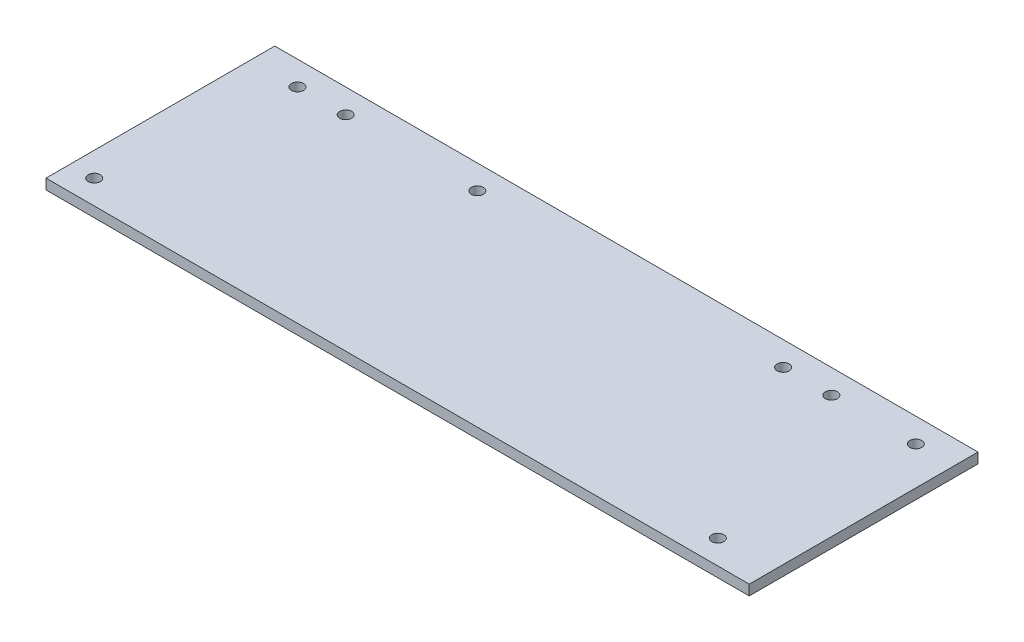
SolidWorks part; units mm, degrees
ref_plane "Front Plane" through (0, 0, 0) normal (0, 0, 1) x (1, 0, 0)
ref_plane "Top Plane" through (0, 0, 0) normal (0, 1, 0) x (1, 0, 0)
ref_plane "Right Plane" through (0, 0, 0) normal (1, 0, 0) x (0, 0, -1)
sketch "Sketch1" plane through (0, 0, 0) normal (0, 1, 0) x (1, 0, 0)
  line L1 (-165.481, -47.5361) -> (164.465, -47.5361)
  line L2 (-165.481, -47.5361) -> (-165.481, 47.5361)
  line L3 (-165.481, 47.5361) -> (164.465, 47.5361)
  line L4 (164.465, -47.5361) -> (164.465, 47.5361)
  line L5 (-165.481, -47.5361) -> (164.465, 47.5361) construction
  line L6 (-165.481, 47.5361) -> (164.465, -47.5361) construction
  line L15 (164.465, -47.5361) -> (114.8334, -47.5361)
  line L16 (164.465, -47.5361) -> (164.465, -42.1259)
  line L19 (-165.481, 47.5361) -> (-205.867, 47.5361)
  line L20 (-165.481, 47.5361) -> (-165.481, -47.5361)
  line L21 (-165.481, -47.5361) -> (-205.867, -47.5361)
  line L22 (-205.867, 47.5361) -> (-205.867, -47.5361)
  line L23 (-205.867, -47.5361) -> (164.465, -47.5361)
  line L24 (-205.867, -47.5361) -> (-205.867, -72.9361)
  line L25 (-205.867, -72.9361) -> (164.465, -72.9361)
  line L26 (164.465, -47.5361) -> (164.465, -72.9361)
  line L34 (86.7283, -47.6885) -> (91.8337, -47.6885) construction
  line L35 (86.5759, -47.5361) -> (91.9861, -47.5361)
  line L36 (86.5759, -47.5361) -> (86.5759, -60.2361)
  line L37 (86.5759, -60.2361) -> (91.9861, -60.2361)
  line L38 (91.9861, -47.5361) -> (91.9861, -60.2361)
  line L39 (91.8337, -47.6885) -> (91.8337, -60.0837) construction
  line L40 (86.7283, -60.0837) -> (91.8337, -60.0837) construction
  line L41 (86.7283, -47.6885) -> (86.7283, -60.0837) construction
  line L42 (-73.787, 47.5361) -> (-73.787, -42.1259)
  line L44 (62.5475, -42.1259) -> (62.5475, 47.5361)
  circle A0 centre (-155.829, 34.8361) radius 3.175
  circle A1 centre (-86.487, 34.8361) radius 3.175
  circle A2 centre (99.949, 34.8361) radius 3.175
  circle A3 centre (144.399, 34.8361) radius 3.175
  circle A4 centre (-181.229, 34.8361) radius 3.175
  circle A5 centre (-193.167, -60.2361) radius 3.175
  circle A6 centre (135.255, -60.2361) radius 3.175
  circle A7 centre (74.549, 34.8361) radius 3.175
  dimension "D10" = 69.342
  dimension "D18" = 40.386
  dimension "D22" = 6.35
  dimension "D23" = 12.7
  dimension "D25" = 12.7
  dimension "D27" = 12.7
  dimension "D6" = 25.4
  dimension "D1" = 329.946
  dimension "D2" = 95.0722
  dimension "D4" = 20.066
  dimension "D5" = 44.45
  dimension "D11" = 9.652
  dimension "D14" = 12.7
  dimension "D15" = 12.7
  dimension "D16" = 12.7
  dimension "D17" = 12.7
  dimension "D19" = 25.4
  dimension "D20" = 12.7
  dimension "D21" = 25.4
  dimension "D24" = 12.7
  dimension "D26" = 29.21
  dimension "D35" = 12.7
  dimension "D36" = 5.4102
  dimension "D38" = 0.1524
extrude "Boss-Extrude1" add sketch "Sketch1" along normal blind 5.4102
